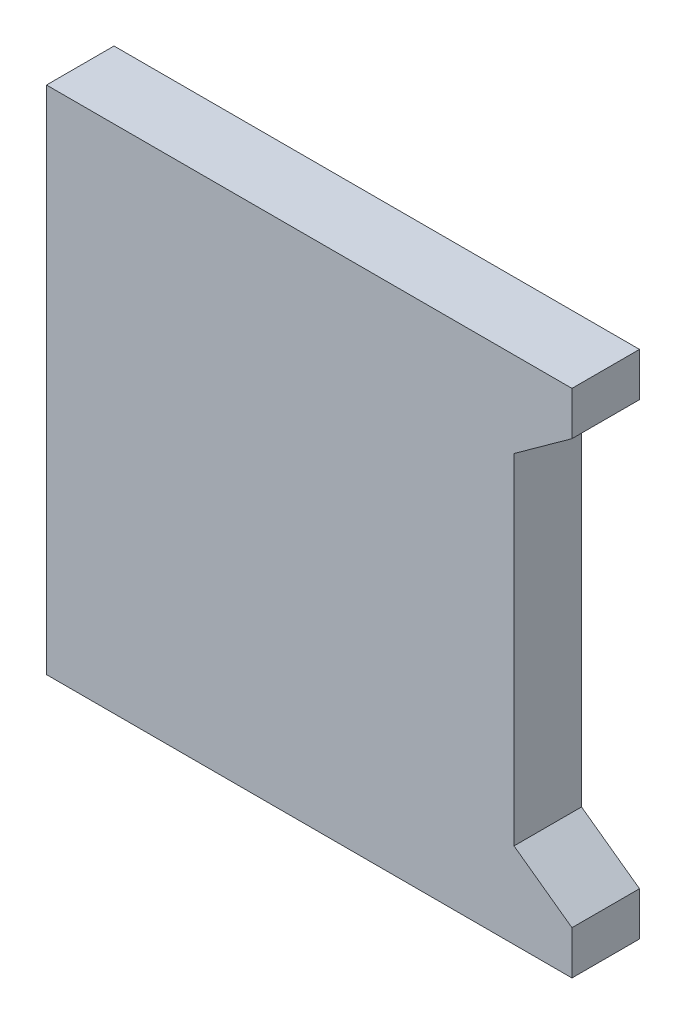
SolidWorks part; units mm, degrees
ref_plane "Front Plane" through (0, 0, 0) normal (0, 0, 1) x (1, 0, 0)
ref_plane "Top Plane" through (0, 0, 0) normal (0, 1, 0) x (1, 0, 0)
ref_plane "Right Plane" through (0, 0, 0) normal (1, 0, 0) x (0, 0, -1)
sketch "Sketch1" plane through (0, 0, 0) normal (0, 0, 1) x (1, 0, 0)
  line L0 (10.73, 9.76) -> (12.06, 10.72)
  line L1 (0, 0) -> (12.06, 0)
  line L2 (0, 0) -> (0, 11.72)
  line L3 (0, 11.72) -> (12.06, 11.72)
  line L4 (12.06, 0) -> (12.06, 1)
  line L5 (10.73, 1.96) -> (10.73, 9.76)
  line L6 (10.73, 1.96) -> (12.06, 1)
  line L7 (12.06, 5.86) -> (10.73, 5.86) construction
  line L8 (12.06, 10.72) -> (12.06, 11.72)
  dimension "D1" = 11.72
  dimension "D2" = 12.06
  dimension "D3" = 1.33
  dimension "D4" = 7.8
  dimension "D5" = 1
  dimension "D6" = 9.72
extrude "Boss-Extrude1" add sketch "Sketch1" along normal blind 1.55
